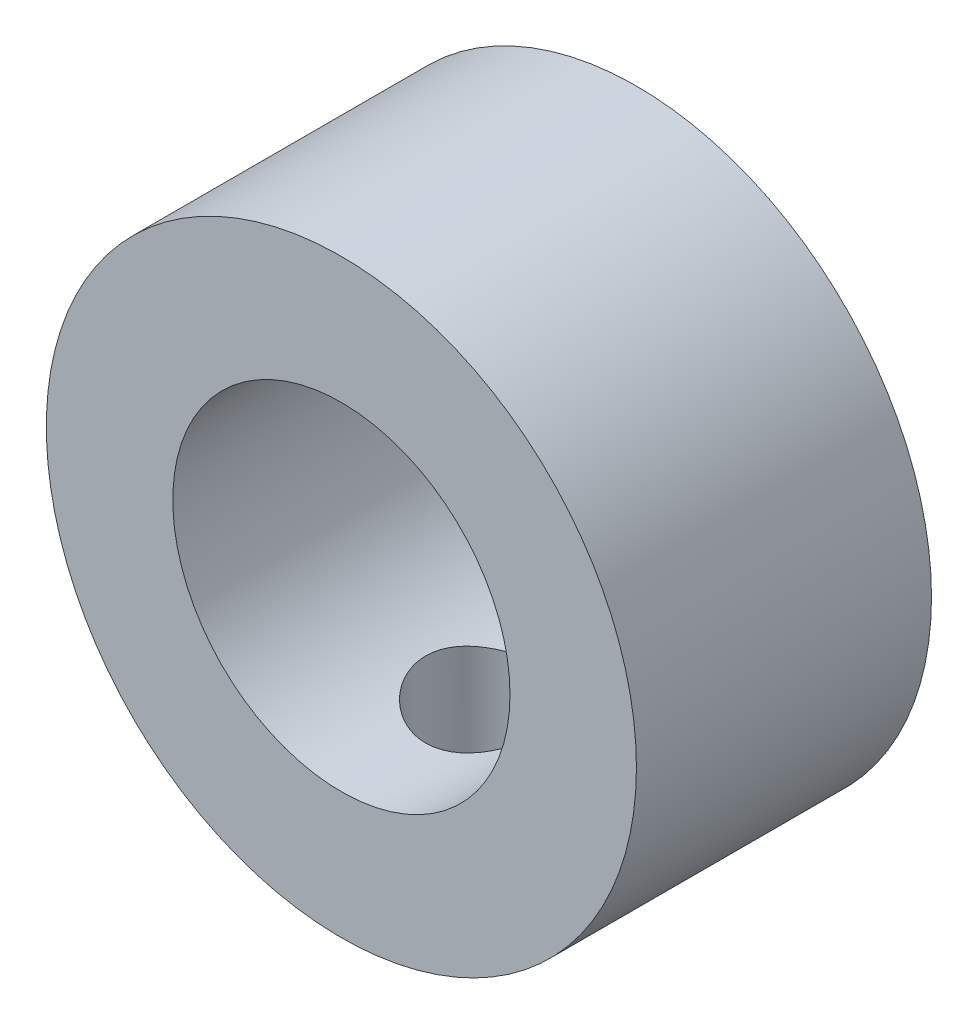
SolidWorks part; units mm, degrees
ref_plane "Ön Düzlem" through (0, 0, 0) normal (0, 0, 1) x (1, 0, 0)
ref_plane "Üst Düzlem" through (0, 0, 0) normal (0, 1, 0) x (1, 0, 0)
ref_plane "Sağ Düzlem" through (0, 0, 0) normal (1, 0, 0) x (0, 0, -1)
sketch "Sketch1" plane through (0, 0, 0) normal (0, 0, 1) x (1, 0, 0)
  circle A0 centre (0, 0) radius 4
  circle A1 centre (0, 0) radius 7
  dimension "D1" = 8
  dimension "D2" = 14
extrude "Boss-Extrude1" add sketch "Sketch1" along normal blind 7
sketch "Sketch2" plane through (0, 0, 0) normal (0, 1, 0) x (1, 0, 0)
  line L0 (-7, 0) -> (-7, -7) construction
  line L1 (7, 0) -> (-7, 0) construction
  circle A0 centre (0, -3.5) radius 1.5
  dimension "D3" = 3
  dimension "D1" = 7
  dimension "D2" = 3.5
extrude "Cut-Extrude1" cut sketch "Sketch2" against normal up to surface (7 mm away)
